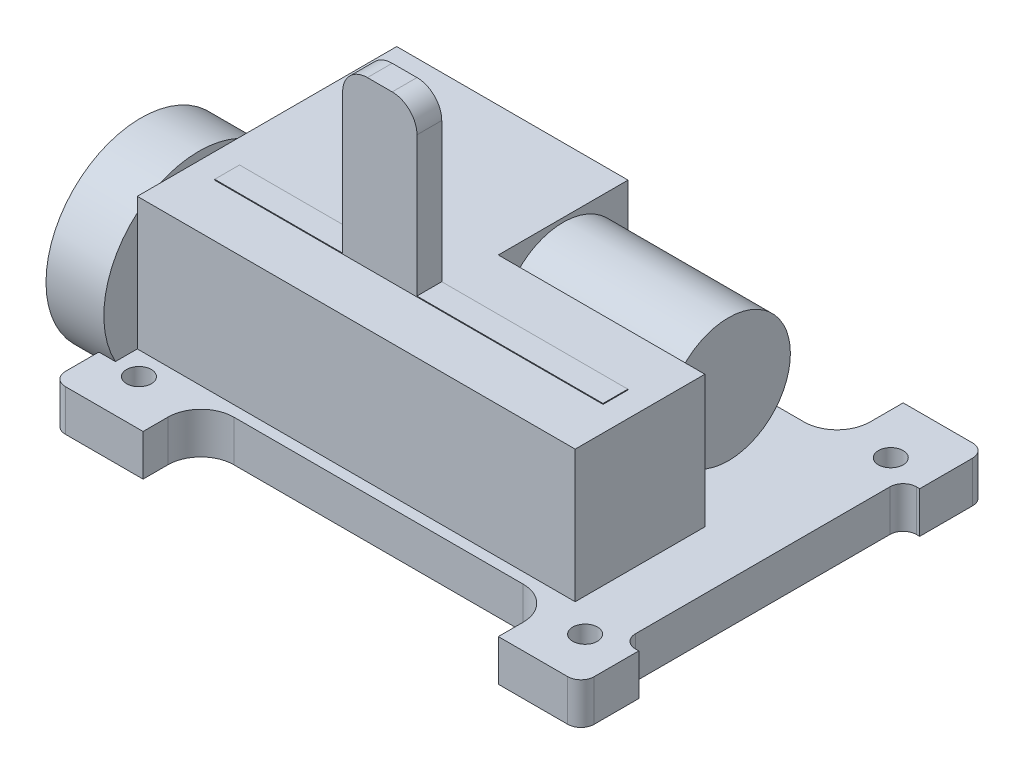
SolidWorks part; units mm, degrees
ref_plane "Front Plane" through (0, 0, 0) normal (0, 0, 1) x (1, 0, 0)
ref_plane "Top Plane" through (0, 0, 0) normal (0, 1, 0) x (1, 0, 0)
ref_plane "Right Plane" through (0, 0, 0) normal (1, 0, 0) x (0, 0, -1)
sketch "Sketch1" plane through (0, 0, 0) normal (0, 1, 0) x (1, 0, 0)
  line L0 (0, 0) -> (1.1, 0)
  line L1 (1.1, 0) -> (1.1, 0.7)
  line L2 (1.1, 0.7) -> (5.4, 0.7)
  line L3 (5.4, 0.7) -> (5.4, 0)
  line L4 (5.4, 0) -> (6.4, 0)
  line L5 (6.4, 0) -> (6.4, 0.7)
  line L6 (6.4, 0.7) -> (6.2, 0.7)
  line L7 (6.2, 0.7) -> (6.2, 4.1)
  line L8 (6.2, 4.1) -> (6.4, 4.1)
  line L9 (6.4, 4.1) -> (6.4, 4.9)
  line L10 (6.4, 4.9) -> (5.4, 4.9)
  line L11 (5.4, 4.9) -> (5.4, 4.1)
  line L12 (5.4, 4.1) -> (1.1, 4.1)
  line L13 (1.1, 4.1) -> (1.1, 4.9)
  line L14 (1.1, 4.9) -> (0, 4.9)
  line L15 (0, 4.9) -> (0, 4.1)
  line L16 (0, 4.1) -> (0.2, 4.1)
  line L17 (0.2, 4.1) -> (0.2, 0.7)
  line L18 (0.2, 0.7) -> (0, 0.7)
  line L19 (0, 0.7) -> (0, 0)
  circle A0 centre (0.5, 4.25) radius 0.15
  circle A1 centre (0.5, 0.55) radius 0.15
  circle A2 centre (5.9, 0.55) radius 0.15
  circle A3 centre (5.9, 4.25) radius 0.15
  dimension "D5" = 0.3
  dimension "D6" = 0.5
  dimension "D7" = 0.5
  dimension "D8" = 0.5
  dimension "D9" = 0.5
  dimension "D1" = 3.4
  dimension "D2" = 6.4
  dimension "D3" = 4.9
  dimension "D4" = 4.3
  dimension "D10" = 1
  dimension "D11" = 0.7
  dimension "D12" = 6
  dimension "D13" = 0.2
extrude "Boss-Extrude1" add sketch "Sketch1" along normal blind 0.5
fillet "Fillet1" radius 0.4 4 edges at (1.1, 0.25, -4.1) (5.4, 0.25, -4.1) (1.1, 0.25, -0.7) (5.4, 0.25, -0.7)
fillet "Fillet2" radius 0.16 8 edges at (0, 0.25, -0.7) (0, 0.25, 0) (6.4, 0.25, 0) (6.2, 0.25, -0.7) (6.2, 0.25, -4.1) (6.4, 0.25, -4.9) (0, 0.25, -4.9) (0.2, 0.25, -4.1)
sketch "Sketch2" plane through (0, 0.5, 0) normal (0, 1, 0) x (1, 0, 0)
  line L0 (0.2, 0.83) -> (5.5, 0.83)
  line L1 (5.5, 0.83) -> (5.5, 2.4)
  line L2 (5.5, 2.4) -> (3, 2.4)
  line L3 (3, 2.4) -> (3, 3.97)
  line L4 (3, 3.97) -> (0.2, 3.97)
  line L5 (0.2, 3.97) -> (0.2, 0.83)
  line L7 (3.25, 4.1) -> (3.25, 0.7) construction
  line L8 (5, 4.1) -> (1.5, 4.1) construction
  line L9 (1.5, 0.7) -> (5, 0.7) construction
  line L10 (0.2, 3.94) -> (0.2, 0.7) construction
  point P7 (0.2, 2.4)
  point P15 (3.25, 2.4)
  dimension "D1" = 3.14
  dimension "D2" = 5.3
  dimension "D3" = 2.8
extrude "Boss-Extrude2" add sketch "Sketch2" along normal blind 1.6
sketch "Sketch3" plane through (3, 0, 0) normal (1, 0, 0) x (0, 0, -1)
  line L0 (2.4, 0.5) -> (3.97, 2.1) construction
  line L1 (2.4, 2.1) -> (3.97, 0.5) construction
  circle A0 centre (3.185, 1.3) radius 0.75
  dimension "D1" = 1.5
extrude "Boss-Extrude7" add sketch "Sketch3" along normal blind 2
sketch "Sketch4" plane through (0, 0, 0) normal (0, -1, 0) x (1, 0, 0)
  line L0 (0.2, -2.32) -> (6.2, -2.32) construction
  line L1 (2.35, -1.42) -> (4.15, -1.42)
  line L2 (2.35, -1.42) -> (2.35, -3.22)
  line L3 (2.35, -3.22) -> (4.15, -3.22)
  line L4 (4.15, -1.42) -> (4.15, -3.22)
  line L7 (3.25, -0.7) -> (3.25, -4.1) construction
  line L8 (1.5, -0.7) -> (5, -0.7) construction
  line L9 (5, -4.1) -> (1.5, -4.1) construction
  line L10 (0.2, -3.94) -> (0.2, -0.7) construction
  line L11 (6.2, -0.86) -> (6.2, -3.94) construction
  point P16 (2.35, -2.32)
  point P17 (3.25, -1.42)
  dimension "D1" = 1.8
  dimension "D2" = 1.8
extrude "Boss-Extrude8" add sketch "Sketch4" along normal blind 0.3
sketch "Sketch5" plane through (0.2, 0, 0) normal (-1, 0, 0) x (0, 0, 1)
  line L0 (-2.32, 0) -> (-0.83, 2.1) construction
  line L2 (-2.32, 2.1) -> (-0.83, 0) construction
  line L4 (-3.94, 0) -> (-0.7, 0) construction
  line L6 (-0.83, 2.1) -> (-0.83, 0) construction
  line L7 (-3.97, 2.1) -> (-0.83, 2.1) construction
  circle A0 centre (-1.575, 1.05) radius 1.15
  dimension "D1" = 2.3
extrude "Boss-Extrude9" add sketch "Sketch5" along normal blind 0.7
sketch "Sketch6" plane through (0, 2.1, 0) normal (0, 1, 0) x (1, 0, 0)
  line L1 (2.048, 1.7672) -> (2.948, 1.7672)
  line L2 (2.048, 1.7672) -> (2.048, 1.4672)
  line L3 (2.048, 1.4672) -> (2.948, 1.4672)
  line L4 (2.948, 1.7672) -> (2.948, 1.4672)
  dimension "D1" = 0.3
  dimension "D2" = 0.9
extrude "Boss-Extrude10" add sketch "Sketch6" along normal blind 2
fillet "Fillet3" radius 0.3 2 edges at (2.048, 4.1, -1.6172) (2.948, 4.1, -1.6172)
sketch "Sketch7" plane through (0, 2.1, 0) normal (0, 1, 0) x (1, 0, 0)
  line L0 (2.348, 1.4672) -> (2.648, 1.4672) construction
  line L1 (0.5, 1.7672) -> (5.2, 1.7672)
  line L2 (0.5, 1.7672) -> (0.5, 1.4672)
  line L3 (0.5, 1.4672) -> (5.2, 1.4672)
  line L4 (5.2, 1.7672) -> (5.2, 1.4672)
  line L5 (2.948, 1.7672) -> (2.048, 1.7672) construction
  line L6 (0.2, 1.106) -> (0.2, 2.044) construction
  line L7 (5.5, 0.83) -> (5.5, 2.4) construction
  dimension "D1" = 0.3
  dimension "D2" = 0.3
extrude "Boss-Extrude11" add sketch "Sketch7" along normal blind 0.01
